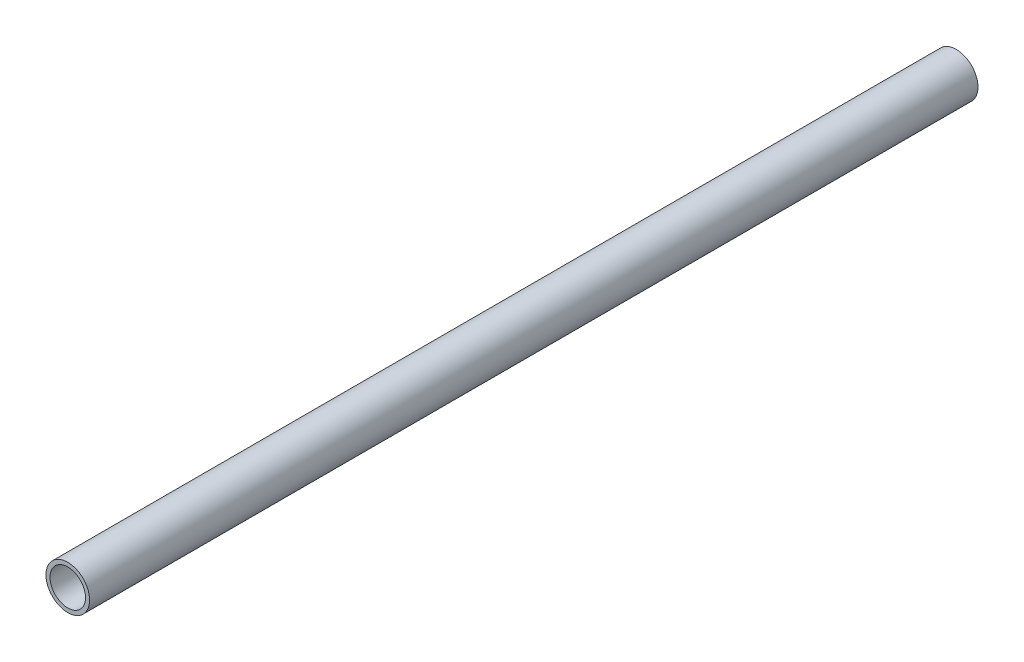
SolidWorks part; units mm, degrees
ref_plane "Alzado" through (0, 0, 0) normal (0, 0, 1) x (1, 0, 0)
ref_plane "Planta" through (0, 0, 0) normal (0, 1, 0) x (1, 0, 0)
ref_plane "Vista lateral" through (0, 0, 0) normal (1, 0, 0) x (0, 0, -1)
sketch "Croquis1" plane through (0, 0, 0) normal (0, 0, 1) x (1, 0, 0)
  circle A0 centre (0, 0) radius 6.6
  circle A1 centre (0, 0) radius 8.1
  dimension "D1" = 16.2
  dimension "D2" = 1.5
extrude "Saliente-Extruir1" add sketch "Croquis1" along normal mid plane 330
